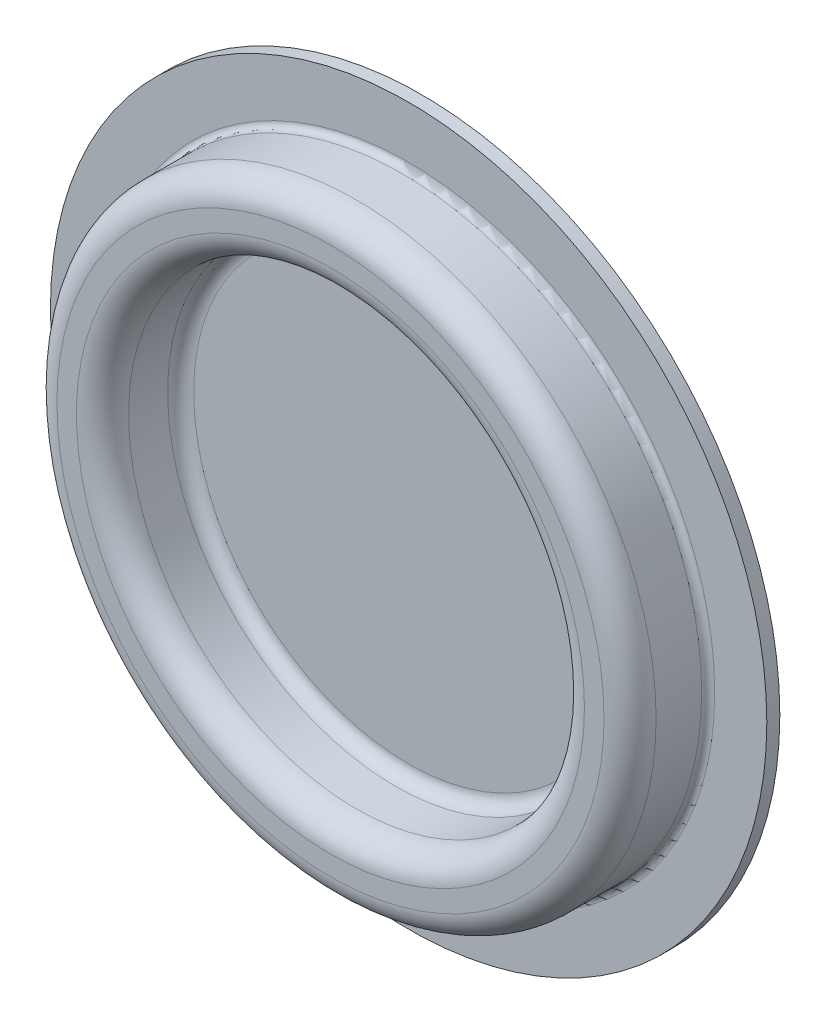
SolidWorks part; units mm, degrees
ref_plane "Alzado" through (0, 0, 0) normal (0, 0, 1) x (1, 0, 0)
ref_plane "Planta" through (0, 0, 0) normal (0, 1, 0) x (1, 0, 0)
ref_plane "Vista lateral" through (0, 0, 0) normal (1, 0, 0) x (0, 0, -1)
sketch "Croquis1" plane through (0, 0, 0) normal (1, 0, 0) x (0, 0, -1)
  line L0 (-74.477, 0) -> (11.1711, 0) construction
  line L1 (-1, 27.5) -> (-1, 23.5)
  line L2 (-1.5, 23) -> (-5, 23)
  line L3 (-7, 21) -> (-7, 19.5)
  line L4 (-5, 17.5) -> (-2, 17.5)
  line L11 (0, 27.5) -> (0, 23.5)
  line L12 (-1.5, 22) -> (-5, 22)
  line L13 (-6, 21) -> (-6, 19.5)
  line L14 (-5, 18.5) -> (-2, 18.5)
  line L15 (-1, 27.5) -> (0, 27.5)
  line L16 (0, 0) -> (-1, 0)
  line L17 (0, 22) -> (-5, 22) construction
  line L18 (0, 27.5) -> (0, 22) construction
  line L19 (-1, 0) -> (-1, 16.5)
  line L21 (0, 0) -> (0, 16.5)
  line L22 (-5, 17.5) -> (-2.3138, 17.5) construction
  line L23 (-5, 18.5) -> (-4.0955, 18.5) construction
  line L24 (-1, -27) -> (-1, 27) construction
  line L25 (-1, 27.5) -> (-1, 23) construction
  line L26 (-1, 23) -> (-5, 23) construction
  arc A1 (-7, 19.5) -> (-5, 17.5) centre (-5, 19.5) ccw
  arc A2 (-5, 23) -> (-7, 21) centre (-5, 21) ccw
  arc A9 (-5, 22) -> (-6, 21) centre (-5, 21) ccw
  arc A10 (-6, 19.5) -> (-5, 18.5) centre (-5, 19.5) ccw
  arc A13 (-1.5, 22) -> (0, 23.5) centre (-1.5, 23.5) ccw
  arc A14 (-0.0223, 24.111) -> (0, 0) centre (-13025.2886, 0) cw construction
  arc A15 (-1.0202, 22.9651) -> (-1, 0) centre (-13025.2886, 0) cw construction
  arc A16 (-4.0955, 18.5) -> (-0.0223, 24.111) centre (-0.0554, 19.8511) cw construction
  arc A17 (-2.3138, 17.5) -> (-1.0202, 22.9651) centre (-0.0554, 19.8511) cw construction
  arc A18 (-2, 17.5) -> (-1, 16.5) centre (-2, 16.5) cw
  arc A19 (-2, 18.5) -> (0, 16.5) centre (-2, 16.5) cw
  arc A20 (-1, 23.5) -> (-1.5, 23) centre (-1.5, 23.5) cw
  dimension "D1" = 1
  dimension "D2" = 1
  dimension "D4" = 2
  dimension "D5" = 2
  dimension "D6" = 1.5
  dimension "D9" = 0.5
  dimension "D3" = 6
  dimension "D7" = 46
  dimension "D8" = 55
  dimension "D10" = 35
revolve "Revolución1" add sketch "Croquis1" angle 360 about L0
